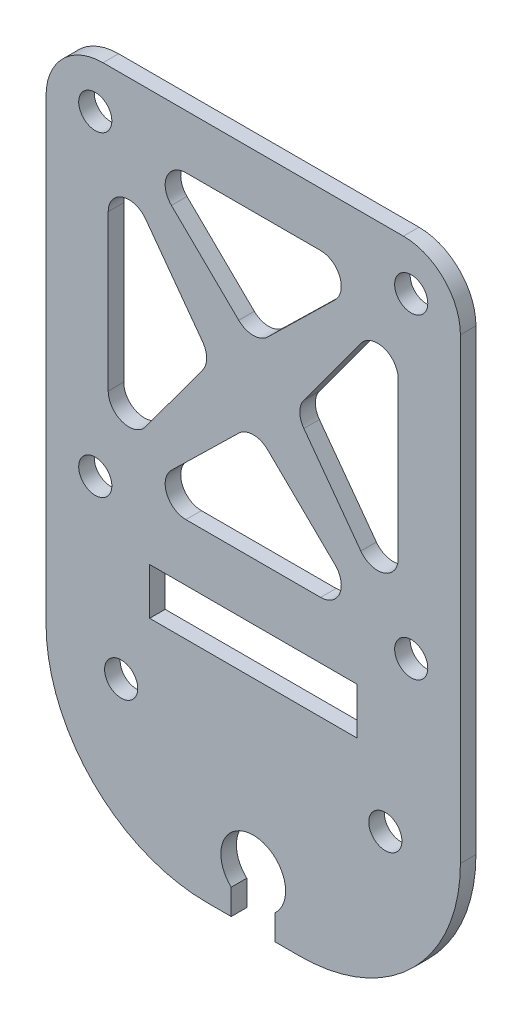
SolidWorks part; units mm, degrees
ref_plane "Front Plane" through (0, 0, 0) normal (0, 0, 1) x (1, 0, 0)
ref_plane "Top Plane" through (0, 0, 0) normal (0, 1, 0) x (1, 0, 0)
ref_plane "Right Plane" through (0, 0, 0) normal (1, 0, 0) x (0, 0, -1)
sketch "Sketch1" plane through (0, 0, 0) normal (0, 0, 1) x (1, 0, 0)
  line L0 (-20, 14.2) -> (-20, -30)
  line L1 (-4.5, -45.5) -> (-2.124, -45.5)
  line L2 (20, -30) -> (20, 14.2)
  line L3 (14.5, 19.7) -> (-14.5, 19.7)
  line L4 (0, 31.9916) -> (0, -70.8358) construction
  line L5 (-10, -20) -> (10, -20)
  line L6 (-10, -20) -> (-10, -24.5)
  line L7 (-10, -24.5) -> (10, -24.5)
  line L8 (10, -20) -> (10, -24.5)
  line L9 (-53.3333, 0) -> (49.6454, 0) construction
  line L10 (-2.124, -43.0423) -> (-2.124, -45.5)
  line L11 (2.124, -43.0423) -> (2.124, -45.5)
  line L12 (2.124, -45.5) -> (4.5, -45.5)
  line L13 (-14, 7.5) -> (-14, -7.5)
  line L14 (-10.3872, -8.6827) -> (-4.8872, -1.1827)
  line L15 (-4.8872, 1.1827) -> (-10.3872, 8.6827)
  line L16 (4.8872, 1.1827) -> (10.3872, 8.6827)
  line L17 (10.3872, -8.6827) -> (4.8872, -1.1827)
  line L18 (14, 7.5) -> (14, -7.5)
  line L19 (-7.8976, 11.0694) -> (-1.3976, 4.7194)
  line L20 (1.3976, 4.7194) -> (7.8976, 11.0694)
  line L21 (6.5, 14.5) -> (-6.5, 14.5)
  line L22 (6.5, -14.5) -> (-6.5, -14.5)
  line L23 (1.3976, -4.7194) -> (7.8976, -11.0694)
  line L24 (-7.8976, -11.0694) -> (-1.3976, -4.7194)
  circle A0 centre (-15.25, 15.25) radius 1.6
  circle A1 centre (15.25, 15.25) radius 1.6
  circle A2 centre (15.25, -15.25) radius 1.6
  circle A3 centre (-15.25, -15.25) radius 1.6
  arc A4 (14.5, 19.7) -> (20, 14.2) centre (14.5, 14.2) cw
  arc A5 (-14.5, 19.7) -> (-20, 14.2) centre (-14.5, 14.2) ccw
  arc A6 (20, -30) -> (4.5, -45.5) centre (4.5, -30) cw
  arc A7 (-4.5, -45.5) -> (-20, -30) centre (-4.5, -30) cw
  arc A8 (2.124, -43.0423) -> (-2.124, -43.0423) centre (0, -40.75) ccw
  circle A9 centre (12.75, -30.95) radius 1.6
  circle A10 centre (-12.75, -30.95) radius 1.6
  arc A11 (-10.3872, 8.6827) -> (-14, 7.5) centre (-12, 7.5) ccw
  arc A12 (-14, -7.5) -> (-10.3872, -8.6827) centre (-12, -7.5) ccw
  arc A13 (-4.8872, -1.1827) -> (-4.8872, 1.1827) centre (-6.5, 0) ccw
  arc A14 (4.8872, -1.1827) -> (4.8872, 1.1827) centre (6.5, 0) cw
  arc A15 (14, -7.5) -> (10.3872, -8.6827) centre (12, -7.5) cw
  arc A16 (10.3872, 8.6827) -> (14, 7.5) centre (12, 7.5) cw
  arc A17 (-1.3976, 4.7194) -> (1.3976, 4.7194) centre (0, 6.15) ccw
  arc A18 (-6.5, 14.5) -> (-7.8976, 11.0694) centre (-6.5, 12.5) ccw
  arc A19 (7.8976, 11.0694) -> (6.5, 14.5) centre (6.5, 12.5) ccw
  arc A20 (7.8976, -11.0694) -> (6.5, -14.5) centre (6.5, -12.5) cw
  arc A21 (-6.5, -14.5) -> (-7.8976, -11.0694) centre (-6.5, -12.5) cw
  arc A22 (-1.3976, -4.7194) -> (1.3976, -4.7194) centre (0, -6.15) cw
  dimension "D4" = 3.2
  dimension "D14" = 5.5
  dimension "D15" = 20
  dimension "D22" = 3.2
  dimension "D17" = 15.5
  dimension "D18" = 6.25
  dimension "D25" = 4
  dimension "D31" = 4
  dimension "D2" = 40.75
  dimension "D3" = 45.5
  dimension "D5" = 15.25
  dimension "D6" = 15.25
  dimension "D7" = 4.45
  dimension "D8" = 30.5
  dimension "D9" = 30.5
  dimension "D10" = 20
  dimension "D11" = 4.5
  dimension "D12" = 20
  dimension "D13" = 20
  dimension "D16" = 10
  dimension "D19" = 2.124
  dimension "D20" = 2.124
  dimension "D21" = 30.95
  dimension "D23" = 12.75
  dimension "D24" = 12.75
  dimension "D26" = 6.5
  dimension "D27" = 7.5
  dimension "D28" = 12
  dimension "D29" = 7.5
  dimension "D30" = 12
  dimension "D32" = 12.5
  dimension "D33" = 6.15
  dimension "D34" = 6.5
  dimension "D35" = 6.5
extrude "Boss-Extrude1" add sketch "Sketch1" along normal mid plane 1.5
